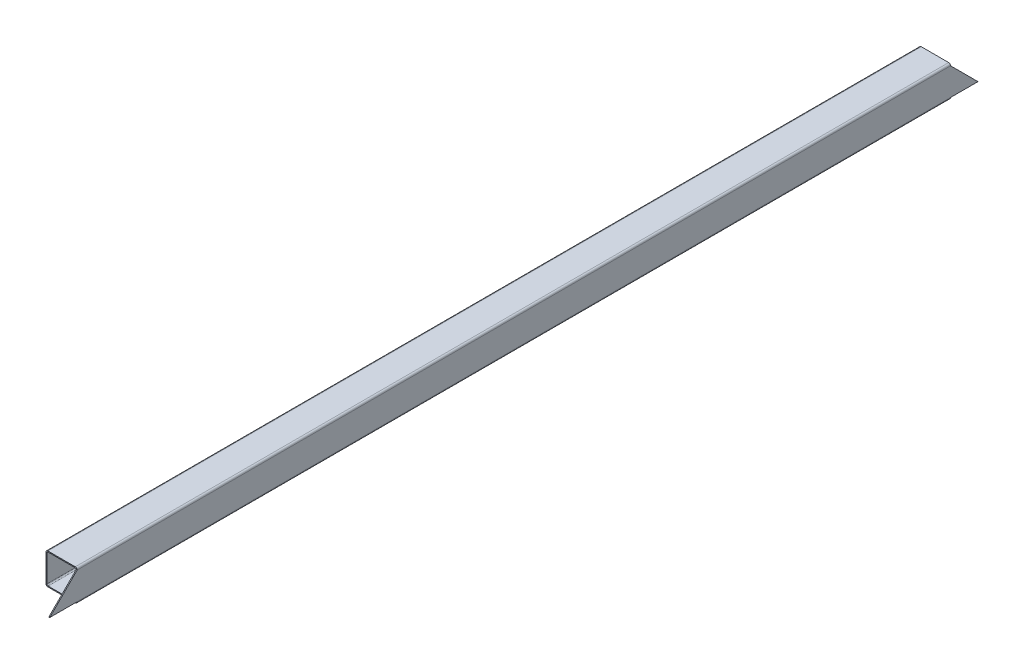
SolidWorks part; units mm, degrees
material "AISI 1020"
ref_plane "Спереди" through (0, 0, 0) normal (0, 0, 1) x (1, 0, 0)
ref_plane "Сверху" through (0, 0, 0) normal (0, 1, 0) x (1, 0, 0)
ref_plane "Справа" through (0, 0, 0) normal (1, 0, 0) x (0, 0, -1)
sketch "Эскиз1" plane through (0, 0, 0) normal (0, 0, 1) x (1, 0, 0)
  line B0 (-44, 50) -> (44, 50)
  line B1 (-50, 44) -> (-50, -44)
  line B2 (-44, -50) -> (44, -50)
  line B3 (50, 44) -> (50, -44)
  line B4 (-50, 50) -> (50, -50) construction
  line B5 (-50, -50) -> (50, 50) construction
  line B6 (-43, 47) -> (43, 47)
  line B7 (-47, 43) -> (-47, -43)
  line B8 (-43, -47) -> (43, -47)
  line B9 (47, 43) -> (47, -43)
  line B10 (-47, 47) -> (47, -47) construction
  line B11 (-47, -47) -> (47, 47) construction
  arc B12 (-50, -44) -> (-44, -50) centre (-44, -44) ccw
  arc B13 (44, -50) -> (50, -44) centre (44, -44) ccw
  arc B14 (44, 50) -> (50, 44) centre (44, 44) cw
  arc B15 (-44, 50) -> (-50, 44) centre (-44, 44) ccw
  arc B16 (-47, -43) -> (-43, -47) centre (-43, -43) ccw
  arc B17 (43, -47) -> (47, -43) centre (43, -43) ccw
  arc B18 (43, 47) -> (47, 43) centre (43, 43) cw
  arc B19 (-43, 47) -> (-47, 43) centre (-43, 43) ccw
sketch_block_instance "Блок1-1"
sketch_block "Блок1" parameters "D3"=6, "D4"=4, "D1"=100, "D2"=3
extrude "Бобышка-Вытянуть1" add sketch "Эскиз1" against normal blind 2800
sketch "Эскиз2" plane through (50, 0, 0) normal (1, 0, 0) x (0, 0, -1)
  line L0 (0, -44) -> (0, 44) construction
  line L1 (0, -44) -> (0, 44)
  line L2 (0, -44) -> (-88, -44)
  line L3 (-88, -44) -> (0, 44)
  line L4 (2800, -44) -> (2800, 44) construction
  line L5 (2800, -44) -> (2800, 44)
  line L6 (2800, -44) -> (2888, -44)
  line L7 (2888, -44) -> (2800, 44)
extrude "Бобышка-Вытянуть2" add sketch "Эскиз2" against normal up to surface (3 mm away) up to face at (47, 0, -1400)
